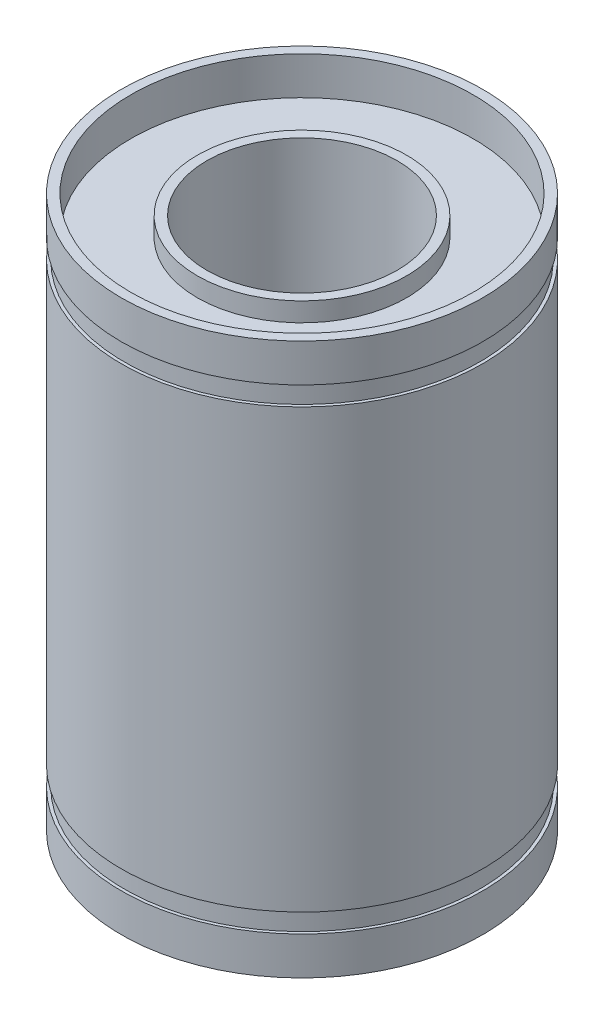
SolidWorks part; units mm, degrees
ref_plane "Front Plane" through (0, 0, 0) normal (0, 0, 1) x (1, 0, 0)
ref_plane "Top Plane" through (0, 0, 0) normal (0, 1, 0) x (1, 0, 0)
ref_plane "Right Plane" through (0, 0, 0) normal (1, 0, 0) x (0, 0, -1)
sketch "Sketch1" plane through (0, 0, 0) normal (0, 1, 0) x (1, 0, 0)
  circle A0 centre (0, 0) radius 5
  circle A1 centre (0, 0) radius 5.4841
extrude "Boss-Extrude1" add sketch "Sketch1" along normal blind 6
sketch "Sketch2" plane through (0, 6, 0) normal (0, 1, 0) x (1, 0, 0)
  circle A0 centre (0, 0) radius 9
  circle A1 centre (0, 0) radius 9.5
extrude "Boss-Extrude2" add sketch "Sketch2" along normal blind 2 separate body
sketch "Sketch3" plane through (0, 0, 0) normal (0, -1, 0) x (1, 0, 0)
  circle A0 centre (0, 0) radius 9.3414
extrude "Boss-Extrude5" add sketch "Sketch3" against normal blind 6
sketch "Sketch4" plane through (0, 0, 0) normal (0, -1, 0) x (1, 0, 0)
  circle A0 centre (0, 0) radius 9.3414
extrude "Cut-Extrude1" cut sketch "Sketch4" against normal blind 5
sketch "Sketch5" plane through (0, 5, 0) normal (0, -1, 0) x (1, 0, 0)
  circle A0 centre (0, 0) radius 9.5
extrude "Boss-Extrude7" add sketch "Sketch5" along normal blind 23
sketch "Sketch7" plane through (0, -18, 0) normal (0, -1, 0) x (1, 0, 0)
  circle A0 centre (0, 0) radius 9.3414
extrude "Boss-Extrude8" add sketch "Sketch7" along normal blind 1
sketch "Sketch8" plane through (0, -19, 0) normal (0, -1, 0) x (1, 0, 0)
  circle A0 centre (0, 0) radius 9.5
extrude "Boss-Extrude9" add sketch "Sketch8" along normal blind 2
sketch "Sketch9" plane through (0, -21, 0) normal (0, -1, 0) x (1, 0, 0)
  circle A0 centre (0, 0) radius 5
extrude "Cut-Extrude2" cut sketch "Sketch9" against normal blind 29
sketch "Sketch10" plane through (0, -21, 0) normal (0, -1, 0) x (1, 0, 0)
  circle A0 centre (0, 0) radius 9
  circle A1 centre (0, 0) radius 5
extrude "Cut-Extrude3" cut sketch "Sketch10" against normal blind 2
sketch "Sketch11" plane through (0, 6, 0) normal (0, 1, 0) x (1, 0, 0)
  circle A0 centre (0, 0) radius 5
  circle A1 centre (0, 0) radius 5.5
extrude "Boss-Extrude10" add sketch "Sketch11" along normal blind 1
sketch "Sketch12" plane through (0, -19, 0) normal (0, -1, 0) x (1, 0, 0)
  circle A0 centre (0, 0) radius 5
  circle A1 centre (0, 0) radius 5.5
extrude "Boss-Extrude11" add sketch "Sketch12" along normal blind 1
